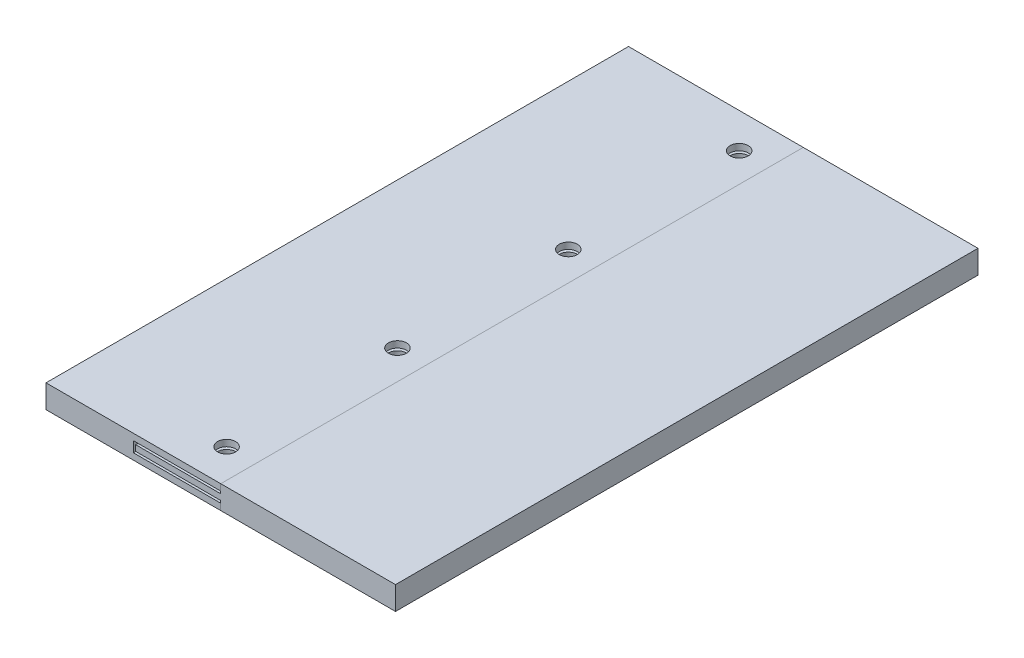
SolidWorks part; units mm, degrees
ref_plane "Front Plane" through (0, 0, 0) normal (0, 0, 1) x (1, 0, 0)
ref_plane "Top Plane" through (0, 0, 0) normal (0, 1, 0) x (1, 0, 0)
ref_plane "Right Plane" through (0, 0, 0) normal (1, 0, 0) x (0, 0, -1)
sketch "Sketch1" plane through (0, 0, 0) normal (0, 1, 0) x (1, 0, 0)
  line L1 (0, 0) -> (-30, 0)
  line L2 (0, 0) -> (0, -100)
  line L3 (0, -100) -> (-30, -100)
  line L4 (-30, 0) -> (-30, -100)
  dimension "D1" = 30
  dimension "D2" = 100
extrude "Boss-Extrude1" add sketch "Sketch1" along normal blind 4
mirror "Mirror1" about plane through (0, 4, 0) normal (-1, 0, 0) of bodies 101
sketch "Sketch3" plane through (0, 0, 100) normal (0, 0, 1) x (1, 0, 0)
  line L0 (0, 4) -> (0, 0) construction
  line L1 (0, 2.9) -> (-15, 2.9)
  line L2 (0, 2.9) -> (0, 1.1)
  line L3 (0, 1.1) -> (-15, 1.1)
  line L4 (-15, 2.9) -> (-15, 1.1)
  line L5 (0, 4) -> (0, 0) construction
  point P10 (0, 2)
  point P11 (0, 2)
  dimension "D1" = 1.8
  dimension "D2" = 15
extrude "Cut-Extrude1" cut sketch "Sketch3" against normal up to next (100 mm away)
sketch "Sketch5" plane through (0, 0, 100) normal (0, 0, 1) x (1, 0, 0)
  line L35 (0, 2.5) -> (0, 1.5)
  line L38 (-14.6, 1.5) -> (0, 1.5)
  line L39 (-14.6, 2.5) -> (-14.6, 1.5)
  line L40 (0, 2.5) -> (-14.6, 2.5)
  line L41 (-14.6, 1.5) -> (0, 1.5)
  line L42 (-14.6, 2.5) -> (-14.6, 1.5)
  line L43 (0, 2.5) -> (-14.6, 2.5)
  dimension "D1" = 0.4
extrude "Boss-Extrude3" add sketch "Sketch5" against normal up to surface (100 mm away) up to face at (15, 2, 0)
sketch "Sketch6" plane through (0, 4, 0) normal (0, 1, 0) x (1, 0, 0)
  line L0 (0, 0) -> (0, -100) construction
  line L2 (0, 0) -> (-30, 0) construction
  line L4 (30, -50) -> (-43.1465, -50) construction
  line L5 (30, 0) -> (30, -100) construction
  line L6 (-5, -94) -> (-5, -64.6667) construction
  line L7 (-5, -64.6667) -> (-5, -35.3333) construction
  line L8 (-5, -35.3333) -> (-5, -6) construction
  circle A0 centre (-5, -6) radius 1.55
  circle A1 centre (-5, -35.3333) radius 1.55
  circle A2 centre (-5, -94) radius 1.55
  circle A3 centre (-5, -64.6667) radius 1.55
  dimension "D1" = 3.1
  dimension "D2" = 6
  dimension "D4" = 5
extrude "Cut-Extrude2" cut sketch "Sketch6" against normal blind 4
chamfer "Chamfer1" [suppressed] distance 0.2 distance2 5
other "Save Bodies1"
